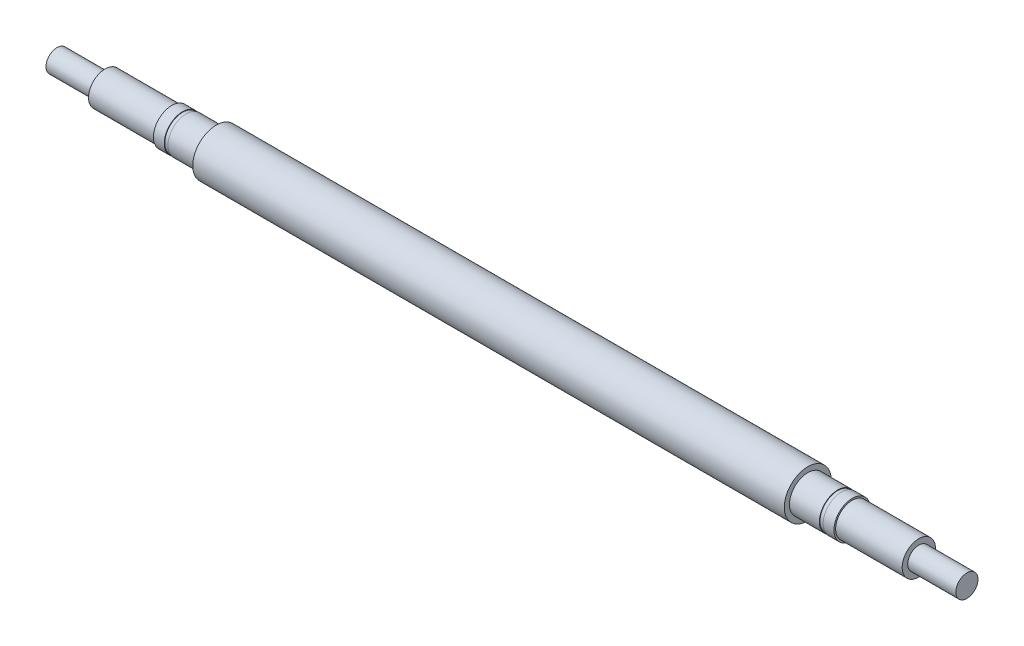
SolidWorks part; units mm, degrees
material "6061 Alloy"
ref_plane "Front Plane" through (0, 0, 0) normal (0, 0, 1) x (1, 0, 0)
ref_plane "Top Plane" through (0, 0, 0) normal (0, 1, 0) x (1, 0, 0)
ref_plane "Right Plane" through (0, 0, 0) normal (1, 0, 0) x (0, 0, -1)
sketch "Sketch1" plane through (0, 0, 0) normal (0, 1, 0) x (1, 0, 0)
  line L0 (123, 0.0537) -> (-123, 0.0537)
  line L2 (79.9761, 6.4037) -> (-79.9761, 6.4037)
  line L3 (-79.9761, 6.4037) -> (-79.9761, 5.0037)
  line L5 (-88.0761, 5.0037) -> (-88.0761, 4.8537)
  line L6 (-88.0761, 4.8537) -> (-89.0761, 4.8537)
  line L7 (-89.0761, 4.8537) -> (-89.0761, 5.0037)
  line L13 (-123, 3.0537) -> (-123, 0.0537)
  line L14 (-89.0761, 5.0037) -> (-92, 5.0037)
  line L15 (-92, 5.0037) -> (-92, 4.5537)
  line L16 (-92, 4.5537) -> (-110, 4.5537)
  line L17 (-110, 4.5537) -> (-110, 3.0537)
  line L18 (-110, 3.0537) -> (-123, 3.0537)
  line L19 (0, -55) -> (0, 55) construction
  line L20 (110, 4.5537) -> (110, 3.0537)
  line L21 (92, 4.5537) -> (110, 4.5537)
  line L22 (92, 5.0037) -> (92, 4.5537)
  line L23 (89.0761, 5.0037) -> (92, 5.0037)
  line L24 (89.0761, 4.8537) -> (89.0761, 5.0037)
  line L25 (88.0761, 4.8537) -> (89.0761, 4.8537)
  line L26 (88.0761, 5.0037) -> (88.0761, 4.8537)
  line L27 (79.9761, 5.0037) -> (88.0761, 5.0037)
  line L28 (79.9761, 6.4037) -> (79.9761, 5.0037)
  line L29 (123, 3.0537) -> (123, 0.0537)
  line L30 (110, 3.0537) -> (123, 3.0537)
  line L31 (0, 6.4037) -> (-15.5, 6.4037) construction
  line L32 (-15.5, 6.4037) -> (-15.5, 5.1674) construction
  line L33 (-15.5, 5.4037) -> (-25.5, 5.4037) construction
  line L34 (-25.5, 5.4037) -> (-25.5, 6.4037) construction
  line L35 (-79.9761, 5.0037) -> (-88.0761, 5.0037)
  dimension "D1" = 1
  dimension "D2" = 4.8
  dimension "D3" = 4.95
  dimension "D4" = 3
revolve "Revolve1" add sketch "Sketch1" angle 360 about L0
sketch "Sketch5" plane through (0, 0, 0) normal (0, 1, 0) x (1, 0, 0)
  line L0 (0, 0) -> (0, 5.35) construction
  line L1 (0, -55) -> (0, 55) construction
  line L2 (0, 5.35) -> (-10.6549, 5.35) construction
  line L3 (-10.6549, 5.35) -> (-20.6549, 5.35)
  line L4 (-20.6549, 5.35) -> (-20.6549, 6.4037)
  line L5 (79.9761, 6.4037) -> (-79.9761, 6.4037) construction
  line L6 (-10.6549, 5.35) -> (-10.6549, 6.4037)
extrude "Cut-Extrude1" cut sketch "Sketch5" against normal through all and the other way through all
